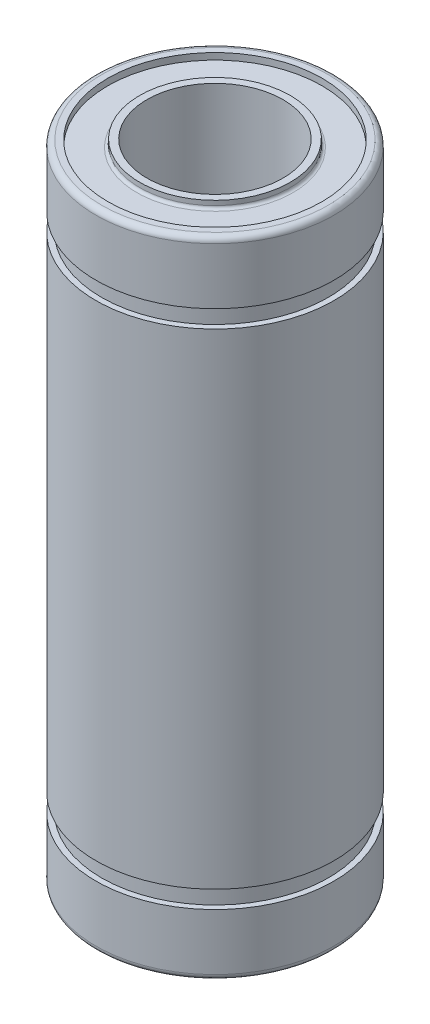
SolidWorks part; units mm, degrees
ref_plane "Front Plane" through (0, 0, 0) normal (0, 0, 1) x (1, 0, 0)
ref_plane "Top Plane" through (0, 0, 0) normal (0, 1, 0) x (1, 0, 0)
ref_plane "Right Plane" through (0, 0, 0) normal (1, 0, 0) x (0, 0, -1)
sketch "Sketch1" plane through (0, 0, 0) normal (0, 0, 1) x (1, 0, 0)
  line L0 (6.635, 28.4804) -> (6, 28.4804)
  line L1 (6, 28.4804) -> (6, -28.4804)
  line L2 (6, -28.4804) -> (6.635, -28.4804)
  line L3 (6.635, -28.4804) -> (6.635, -28.074)
  line L4 (6.889, -27.82) -> (9.435, -27.82)
  line L5 (9.435, -27.82) -> (9.435, -28.4)
  line L6 (9.435, -28.4) -> (9.982, -28.4)
  line L7 (10.49, -27.892) -> (10.49, -22.93)
  line L8 (10.49, -22.93) -> (10, -22.93)
  line L9 (10, -22.93) -> (10, -21.38)
  line L10 (10, -21.38) -> (10.49, -21.38)
  line L11 (10.49, -21.38) -> (10.49, 21.38)
  line L12 (10.49, 21.38) -> (10, 21.38)
  line L13 (10, 21.38) -> (10, 22.93)
  line L14 (10, 22.93) -> (10.49, 22.93)
  line L15 (10.49, 22.93) -> (10.49, 27.892)
  line L16 (9.982, 28.4) -> (9.435, 28.4)
  line L17 (9.435, 28.4) -> (9.435, 27.82)
  line L18 (9.435, 27.82) -> (6.889, 27.82)
  line L19 (6.635, 28.074) -> (6.635, 28.4804)
  line L20 (0, 28.4804) -> (0, -28.4804) construction
  arc A0 (6.635, -28.074) -> (6.889, -27.82) centre (6.889, -28.074) cw
  arc A1 (9.982, -28.4) -> (10.49, -27.892) centre (9.982, -27.892) ccw
  arc A2 (10.49, 27.892) -> (9.982, 28.4) centre (9.982, 27.892) ccw
  arc A3 (6.889, 27.82) -> (6.635, 28.074) centre (6.889, 28.074) cw
revolve "Revolve1" add sketch "Sketch1" angle 360 about L20
